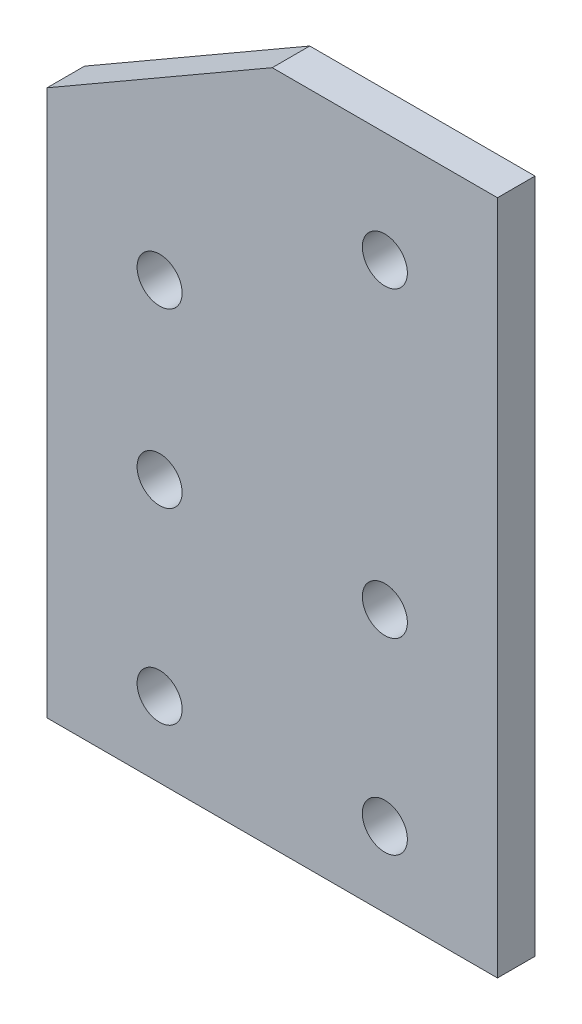
SolidWorks part; units mm, degrees
ref_plane "Front Plane" through (0, 0, 0) normal (0, 0, 1) x (1, 0, 0)
ref_plane "Top Plane" through (0, 0, 0) normal (0, 1, 0) x (1, 0, 0)
ref_plane "Right Plane" through (0, 0, 0) normal (1, 0, 0) x (0, 0, -1)
sketch "Sketch1" plane through (0, 0, 0) normal (0, 0, 1) x (1, 0, 0)
  line L0 (0, 92.303) -> (38.1, 114.3)
  line L1 (0, 0) -> (76.2, 0)
  line L2 (0, 0) -> (0, 92.303)
  line L4 (76.2, 0) -> (76.2, 114.3)
  line L5 (38.1, 114.3) -> (76.2, 114.3)
  line L6 (57.15, 95.657) -> (19.05, 73.66) construction
  line L7 (19.05, 73.66) -> (76.2, 73.66) construction
  circle A0 centre (19.05, 73.66) radius 3.81
  circle A1 centre (57.15, 95.657) radius 3.81
  circle A2 centre (19.05, 44.45) radius 3.81
  circle A3 centre (19.05, 12.7) radius 3.81
  circle A4 centre (57.15, 44.45) radius 3.81
  circle A5 centre (57.15, 12.7) radius 3.81
  point P23 (57.15, 114.3)
  point P25 (19.05, 103.3015)
  dimension "D5" = 7.62
  dimension "D1" = 114.3
  dimension "D2" = 76.2
  dimension "D3" = 30
  dimension "D4" = 38.1
  dimension "D6" = 31.75
  dimension "D7" = 29.21
  dimension "D8" = 30
  dimension "D9" = 12.7
extrude "Boss-Extrude1" add sketch "Sketch1" along normal blind 6.35
